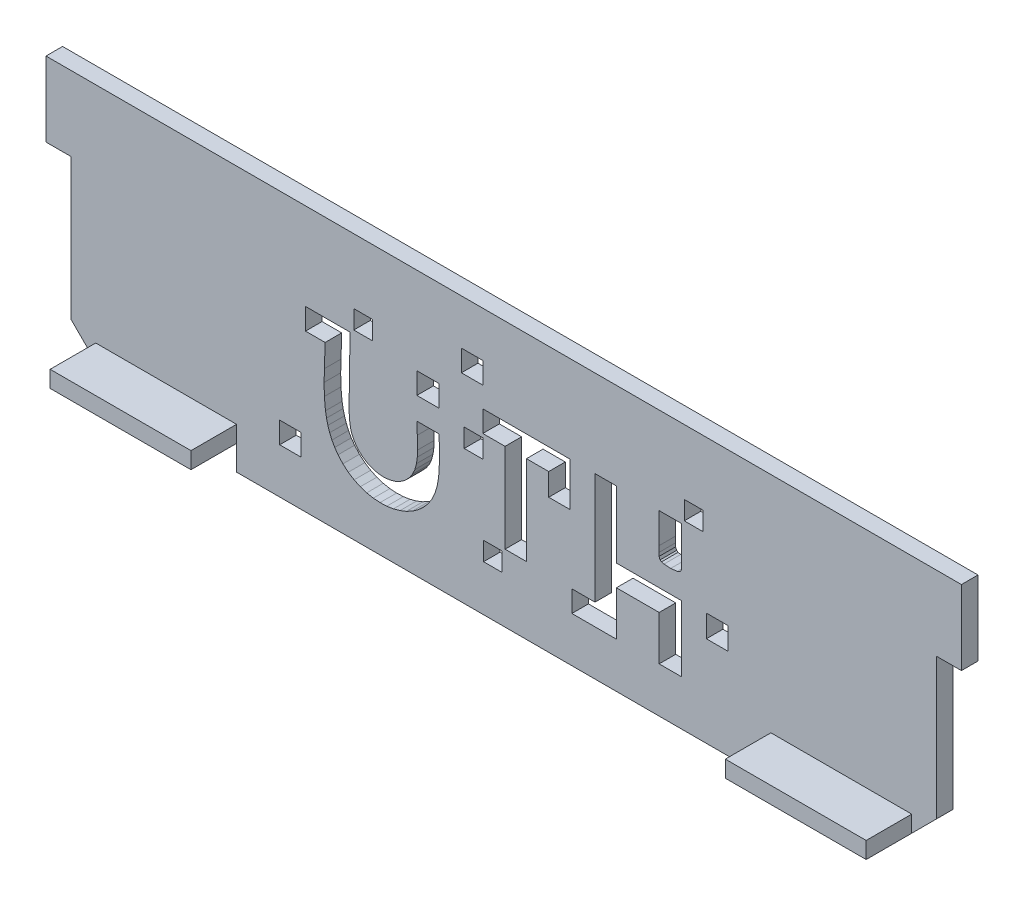
SolidWorks part; units mm, degrees
ref_plane "Front Plane" through (0, 0, 0) normal (0, 0, 1) x (1, 0, 0)
ref_plane "Top Plane" through (0, 0, 0) normal (0, 1, 0) x (1, 0, 0)
ref_plane "Right Plane" through (0, 0, 0) normal (1, 0, 0) x (0, 0, -1)
sketch "Sketch1" plane through (0, 0, 0) normal (0, 0, 1) x (1, 0, 0)
  line L0 (0, 0) -> (0, 32) construction
  line L1 (-32.25, 0) -> (32.25, 0)
  line L2 (32.25, 0) -> (32.25, 3)
  line L3 (32.25, 3) -> (49.25, 3)
  line L4 (49.25, 3) -> (52.25, 6)
  line L5 (55.25, 32) -> (55.25, 23)
  line L6 (55.25, 32) -> (-55.25, 32)
  line L7 (55.25, 23) -> (52.25, 23)
  line L8 (52.25, 23) -> (52.25, 6)
  line L9 (-52.25, 23) -> (-52.25, 6)
  line L10 (-55.25, 23) -> (-52.25, 23)
  line L11 (-55.25, 32) -> (-55.25, 23)
  line L12 (-49.25, 3) -> (-52.25, 6)
  line L13 (-32.25, 3) -> (-49.25, 3)
  line L14 (-32.25, 0) -> (-32.25, 3)
  dimension "D1" = 45
  dimension "D2" = 64.5
  dimension "D3" = 32
  dimension "D4" = 3
  dimension "D5" = 3
  dimension "D6" = 3
  dimension "D7" = 17
extrude "Boss-Extrude1" add sketch "Sketch1" along normal blind 2
sketch "Sketch2" plane through (0, 0, 2) normal (0, 0, 1) x (1, 0, 0)
  line L0 (0, 0) -> (0, 32) construction
  line L1 (-49.25, 3) -> (-32.25, 3)
  line L2 (-49.25, 3) -> (-49.25, 5)
  line L3 (-49.25, 5) -> (-32.25, 5)
  line L4 (-32.25, 3) -> (-32.25, 5)
  line L5 (55.25, 32) -> (-55.25, 32) construction
  line L6 (49.25, 5) -> (32.25, 5)
  line L7 (32.25, 3) -> (32.25, 5)
  line L8 (49.25, 3) -> (32.25, 3)
  line L9 (49.25, 3) -> (49.25, 5)
  dimension "D1" = 2
extrude "Boss-Extrude2" add sketch "Sketch2" along normal blind 5.5
sketch "Sketch3" plane through (0, 0, 0) normal (0, 0, -1) x (-1, 0, 0)
  line L0 (2.5269, 26.5376) -> (2.5269, 23.957)
  line L1 (2.5269, 23.957) -> (5.1075, 23.957)
  line L2 (5.1075, 23.957) -> (5.1075, 26.5376)
  line L3 (5.1075, 26.5376) -> (2.5269, 26.5376)
  line L4 (-24.0364, 24.172) -> (-24.0364, 21.9307)
  line L5 (-24.0364, 21.9307) -> (-21.7952, 21.9307)
  line L6 (-21.4516, 21.4839) -> (-21.4516, 17.9355)
  line L7 (-21.4516, 17.9355) -> (-21.4902, 17.1869)
  line L8 (-21.4902, 17.1869) -> (-21.4768, 16.7976)
  line L9 (-21.4768, 16.7976) -> (-21.3867, 16.4643)
  line L10 (-21.3867, 16.4643) -> (-21.2316, 16.328)
  line L11 (-21.2316, 16.328) -> (-20.9471, 16.2288)
  line L12 (-20.9471, 16.2288) -> (-20.1576, 16.14)
  line L13 (-20.1576, 16.14) -> (-19.3545, 16.1942)
  line L14 (-19.3545, 16.1942) -> (-19.0529, 16.2736)
  line L15 (-19.0529, 16.2736) -> (-18.8739, 16.3875)
  line L16 (-18.8739, 16.3875) -> (-18.751, 16.6925)
  line L17 (-18.751, 16.6925) -> (-18.7248, 17.0839)
  line L18 (-18.7248, 17.0839) -> (-18.7634, 17.828)
  line L19 (-18.7634, 17.828) -> (-18.7634, 21.4839)
  line L20 (-18.7634, 21.4839) -> (-21.4516, 21.4839)
  line L21 (-21.7952, 21.9307) -> (-21.7952, 24.172)
  line L22 (-21.7952, 24.172) -> (-24.0364, 24.172)
  line L23 (15.8602, 24.172) -> (15.8602, 21.9307)
  line L24 (15.8602, 21.9307) -> (18.1015, 21.9307)
  line L25 (18.1015, 21.9307) -> (18.1015, 24.172)
  line L26 (18.1015, 24.172) -> (15.8602, 24.172)
  line L27 (-13.6021, 21.4839) -> (-13.6021, 13.4194)
  line L28 (-13.6021, 13.4194) -> (-21.4516, 13.4194)
  line L29 (-21.4516, 13.4194) -> (-21.4516, 5.4624)
  line L30 (-21.4516, 5.4624) -> (-18.7634, 5.4624)
  line L31 (-18.7634, 5.4624) -> (-18.7634, 10.8387)
  line L32 (-18.7634, 10.8387) -> (-13.6021, 10.8387)
  line L33 (-13.6021, 10.8387) -> (-13.6021, 5.4624)
  line L34 (-13.6021, 5.4624) -> (-8.2258, 5.4624)
  line L35 (-8.2258, 5.4624) -> (-8.2258, 8.043)
  line L36 (-8.2258, 8.043) -> (-11.0215, 8.043)
  line L37 (-11.0215, 8.043) -> (-11.0215, 21.4839)
  line L38 (-11.0215, 21.4839) -> (-13.6021, 21.4839)
  line L39 (-8.0107, 21.4839) -> (-8.0107, 16.2151)
  line L40 (-8.0107, 16.2151) -> (-5.4301, 16.2151)
  line L41 (-5.4301, 16.2151) -> (-5.4301, 18.9032)
  line L42 (-5.4301, 18.9032) -> (-2.7419, 18.9032)
  line L43 (-2.7419, 18.9032) -> (-2.7419, 8.1506)
  line L44 (-2.7419, 8.1506) -> (-0.1613, 8.1506)
  line L45 (-0.1613, 8.1506) -> (-0.1613, 18.9032)
  line L46 (-0.1613, 18.9032) -> (2.5269, 18.9032)
  line L47 (4.7682, 18.4563) -> (2.5269, 18.4563)
  line L48 (2.5269, 16.2151) -> (4.7682, 16.2151)
  line L49 (4.7682, 16.2151) -> (4.7682, 18.4563)
  line L50 (2.5269, 18.4563) -> (2.5269, 16.2151)
  line L51 (2.5269, 18.9032) -> (2.5269, 21.4839)
  line L52 (2.5269, 21.4839) -> (-8.0107, 21.4839)
  line L53 (7.7957, 21.4839) -> (7.7957, 18.9032)
  line L54 (7.7957, 18.9032) -> (10.4838, 18.9032)
  line L55 (10.4838, 18.9032) -> (10.4838, 21.4839)
  line L56 (10.4838, 21.4839) -> (7.7957, 21.4839)
  line L57 (18.5483, 21.4839) -> (18.6021, 17.9367)
  line L58 (18.6021, 17.9367) -> (18.6559, 14.3871)
  line L59 (18.6559, 14.3871) -> (18.6628, 13.4092)
  line L60 (18.6628, 13.4092) -> (18.6304, 12.4079)
  line L61 (18.6304, 12.4079) -> (18.4789, 11.4285)
  line L62 (18.4789, 11.4285) -> (18.3335, 10.9611)
  line L63 (18.3335, 10.9611) -> (18.1285, 10.5161)
  line L64 (18.1285, 10.5161) -> (17.8116, 10.023)
  line L65 (17.8116, 10.023) -> (17.445, 9.5935)
  line L66 (17.445, 9.5935) -> (17.0354, 9.228)
  line L67 (17.0354, 9.228) -> (16.59, 8.9266)
  line L68 (16.59, 8.9266) -> (16.1158, 8.6896)
  line L69 (16.1158, 8.6896) -> (15.6198, 8.5173)
  line L70 (15.6198, 8.5173) -> (15.109, 8.41)
  line L71 (15.109, 8.41) -> (14.5906, 8.3679)
  line L72 (14.5906, 8.3679) -> (14.0714, 8.3912)
  line L73 (14.0714, 8.3912) -> (13.5586, 8.4802)
  line L74 (13.5586, 8.4802) -> (13.0592, 8.6352)
  line L75 (13.0592, 8.6352) -> (12.5801, 8.8564)
  line L76 (12.5801, 8.8564) -> (12.1285, 9.1441)
  line L77 (12.1285, 9.1441) -> (11.7114, 9.4985)
  line L78 (11.7114, 9.4985) -> (11.3357, 9.9199)
  line L79 (11.3357, 9.9199) -> (11.0085, 10.4086)
  line L80 (11.0085, 10.4086) -> (10.7161, 11.0525)
  line L81 (10.7161, 11.0525) -> (10.5299, 11.7491)
  line L82 (10.5299, 11.7491) -> (10.4294, 12.4836)
  line L83 (10.4294, 12.4836) -> (10.3936, 13.2415)
  line L84 (10.3936, 13.2415) -> (10.4336, 14.7691)
  line L85 (10.4336, 14.7691) -> (10.4838, 16.2151)
  line L86 (10.4838, 16.2151) -> (7.7957, 16.2151)
  line L87 (7.7957, 16.2151) -> (7.764, 14.3733)
  line L88 (7.764, 14.3733) -> (7.7869, 12.4719)
  line L89 (7.7869, 12.4719) -> (7.8743, 11.5311)
  line L90 (7.8743, 11.5311) -> (8.0418, 10.6141)
  line L91 (8.0418, 10.6141) -> (8.3116, 9.7338)
  line L92 (8.3116, 9.7338) -> (8.7058, 8.9032)
  line L93 (8.7058, 8.9032) -> (9.1823, 8.1909)
  line L94 (9.1823, 8.1909) -> (9.7356, 7.5575)
  line L95 (9.7356, 7.5575) -> (10.3558, 7.0046)
  line L96 (10.3558, 7.0046) -> (11.0331, 6.5341)
  line L97 (11.0331, 6.5341) -> (11.7575, 6.1477)
  line L98 (11.7575, 6.1477) -> (12.519, 5.847)
  line L99 (12.519, 5.847) -> (13.3078, 5.6338)
  line L100 (13.3078, 5.6338) -> (14.114, 5.5098)
  line L101 (14.114, 5.5098) -> (14.9276, 5.4768)
  line L102 (14.9276, 5.4768) -> (15.7387, 5.5364)
  line L103 (15.7387, 5.5364) -> (16.5374, 5.6903)
  line L104 (16.5374, 5.6903) -> (17.3138, 5.9403)
  line L105 (17.3138, 5.9403) -> (18.058, 6.2881)
  line L106 (18.058, 6.2881) -> (18.7601, 6.7354)
  line L107 (18.7601, 6.7354) -> (19.41, 7.284)
  line L108 (19.41, 7.284) -> (19.9981, 7.9355)
  line L109 (19.9981, 7.9355) -> (20.3985, 8.5066)
  line L110 (20.3985, 8.5066) -> (20.7322, 9.1102)
  line L111 (20.7322, 9.1102) -> (21.0049, 9.7427)
  line L112 (21.0049, 9.7427) -> (21.2222, 10.4004)
  line L113 (21.2222, 10.4004) -> (21.3897, 11.0794)
  line L114 (21.3897, 11.0794) -> (21.5131, 11.7762)
  line L115 (21.5131, 11.7762) -> (21.6499, 13.2082)
  line L116 (21.6499, 13.2082) -> (21.6778, 14.6665)
  line L117 (21.6778, 14.6665) -> (21.6419, 16.1216)
  line L118 (21.6419, 16.1216) -> (21.5591, 18.9032)
  line L119 (21.5591, 18.9032) -> (23.9247, 18.9032)
  line L120 (23.9247, 18.9032) -> (23.9247, 21.4839)
  line L121 (23.9247, 21.4839) -> (18.5483, 21.4839)
  line L122 (-27.043, 13.6226) -> (-27.043, 10.9344)
  line L123 (-27.043, 10.9344) -> (-24.4623, 10.9344)
  line L124 (-24.4623, 10.9344) -> (-24.4623, 13.6226)
  line L125 (-24.4623, 13.6226) -> (-27.043, 13.6226)
  line L126 (0.1924, 7.7845) -> (0.1923, 5.5432)
  line L127 (0.1923, 5.5432) -> (2.4336, 5.5433)
  line L128 (2.4336, 5.5433) -> (2.4337, 7.7846)
  line L129 (2.4337, 7.7846) -> (0.1924, 7.7845)
  line L130 (24.4623, 8.043) -> (24.4623, 5.4624)
  line L131 (24.4623, 5.4624) -> (27.043, 5.4624)
  line L132 (27.043, 5.4624) -> (27.043, 8.043)
  line L133 (27.043, 8.043) -> (24.4623, 8.043)
  line L134 (0, 0) -> (0, 32) construction
  line L135 (-27.043, 26.5376) -> (27.043, 26.5376) construction
  line L136 (-27.043, 26.5376) -> (-27.043, 5.4624) construction
  line L137 (-27.043, 5.4624) -> (27.043, 5.4624) construction
  line L138 (27.043, 26.5376) -> (27.043, 5.4624) construction
  line L139 (0, 5.4624) -> (0, 26.5376) construction
  line L140 (-27.043, 16) -> (27.043, 16) construction
  line L141 (-52.25, 6) -> (-52.25, 23) construction
  line L142 (-52.25, 16) -> (52.25, 16) construction
  line L143 (-55.25, 32) -> (55.25, 32) construction
  line L144 (52.25, 23) -> (52.25, 6) construction
  point P138 (0, 16)
  point P182 (0, 16)
extrude "Cut-Extrude1" cut sketch "Sketch3" against normal blind 5
